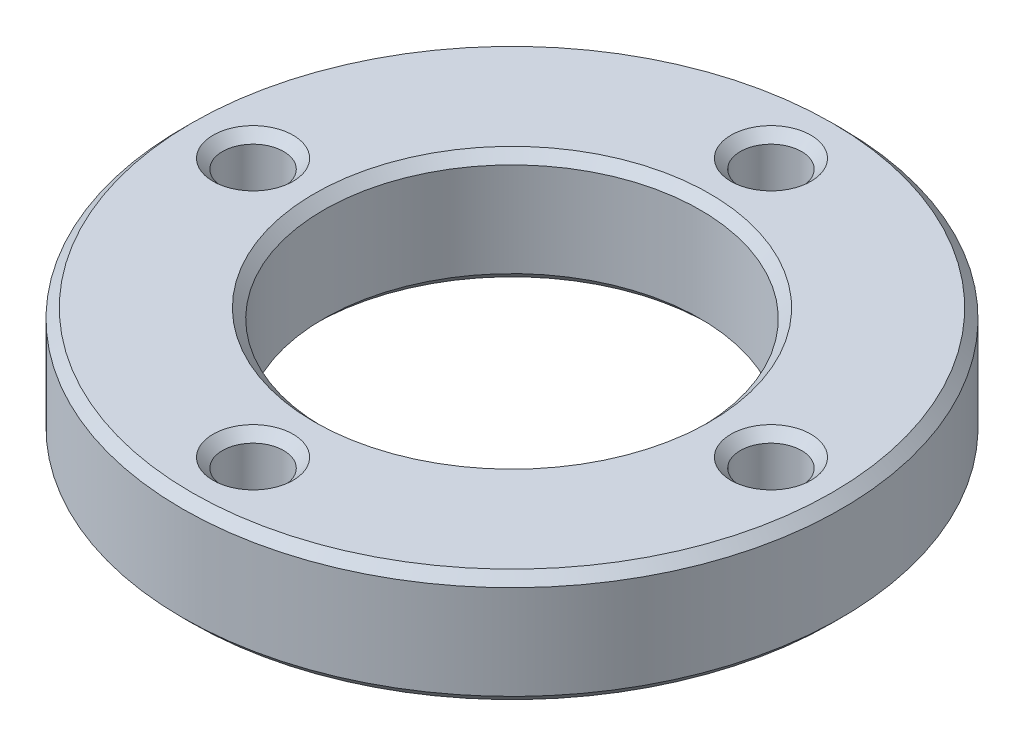
SolidWorks part; units mm, degrees
material "ABS"
ref_plane "Front Plane" through (0, 0, 0) normal (0, 0, 1) x (1, 0, 0)
ref_plane "Top Plane" through (0, 0, 0) normal (0, 1, 0) x (1, 0, 0)
ref_plane "Right Plane" through (0, 0, 0) normal (1, 0, 0) x (0, 0, -1)
sketch "Sketch1" plane through (0, 0, 0) normal (0, 1, 0) x (1, 0, 0)
  line L0 (-74.6477, 0) -> (75.0914, 0) construction
  line L1 (0, -55.6808) -> (0, 61.0048) construction
  circle A0 centre (0, 0) radius 20
  circle A1 centre (0, 0) radius 35
  circle A2 centre (27.5, 0) radius 3.25
  circle A3 centre (0, -27.5) radius 3.25
  circle A4 centre (-27.5, 0) radius 3.25
  circle A5 centre (0, 27.5) radius 3.25
  dimension "D1" = 40
  dimension "D2" = 70
  dimension "D3" = 6.5
  dimension "D4" = 6.5
  dimension "D5" = 6.5
  dimension "D6" = 6.5
  dimension "D7" = 27.5
  dimension "D8" = 27.5
  dimension "D9" = 27.5
  dimension "D10" = 27.5
extrude "Boss-Extrude1" add sketch "Sketch1" along normal blind 12
chamfer "Chamfer1" distance 1 angle 45 12 edges at (0, 0, -24.25) (-27.5, 0, 3.25) (0, 0, 30.75) (27.5, 0, 3.25) (0, 0, 20) (0, 0, 35) (0, 12, -24.25) (0, 12, 30.75) (0, 12, 20) (0, 12, 35) (27.5, 12, 3.25) (-27.5, 12, 3.25)
